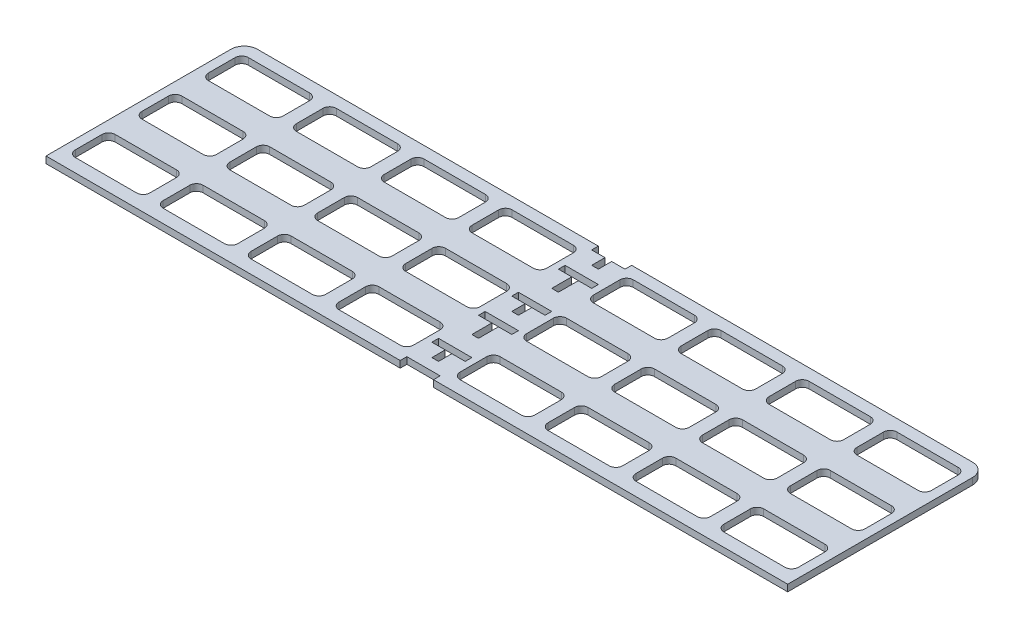
SolidWorks part; units mm, degrees
material "Balsa"
ref_plane "Front Plane" through (0, 0, 0) normal (0, 0, 1) x (1, 0, 0)
ref_plane "Top Plane" through (0, 0, 0) normal (0, 1, 0) x (1, 0, 0)
ref_plane "Right Plane" through (0, 0, 0) normal (1, 0, 0) x (0, 0, -1)
sketch "Sketch1" plane through (0, 0, 0) normal (0, 1, 0) x (1, 0, 0)
  line L0 (0, 0) -> (350.52, 0)
  line L1 (337.82, 188.976) -> (0, 188.976)
  line L3 (350.52, 0) -> (350.52, 176.276)
  line L4 (0, 188.976) -> (0, 169.926)
  line L5 (0, 169.926) -> (-3.175, 169.926)
  line L6 (-3.175, 169.926) -> (-3.175, 150.876)
  line L7 (-3.175, 150.876) -> (0, 150.876)
  line L8 (0, 150.876) -> (0, 131.826)
  line L9 (0, 131.826) -> (-3.175, 131.826)
  line L10 (-3.175, 131.826) -> (-3.175, 112.776)
  line L11 (-3.175, 112.776) -> (0, 112.776)
  line L12 (0, 112.776) -> (0, 93.726)
  line L13 (0, 93.726) -> (-3.175, 93.726)
  line L14 (-3.175, 93.726) -> (-3.175, 74.676)
  line L15 (-3.175, 74.676) -> (0, 74.676)
  line L16 (0, 74.676) -> (0, 55.626)
  line L17 (0, 55.626) -> (-3.175, 55.626)
  line L18 (-3.175, 55.626) -> (-3.175, 36.576)
  line L19 (-3.175, 36.576) -> (0, 36.576)
  line L20 (0, 36.576) -> (0, 17.526)
  line L21 (0, 17.526) -> (-3.175, 17.526)
  line L22 (-3.175, 17.526) -> (-3.175, 0)
  line L23 (-3.175, 0) -> (0, 0)
  arc A0 (337.82, 188.976) -> (350.52, 176.276) centre (337.82, 176.276) cw
  point P7 (350.52, 188.976)
  dimension "D4" = 12.7
  dimension "D2" = 350.52
  dimension "D3" = 188.976
  dimension "D5" = 19.05
  dimension "D6" = 19.05
  dimension "D7" = 3.175
  dimension "D8" = 19.05
  dimension "D9" = 19.05
  dimension "D10" = 19.05
  dimension "D11" = 19.05
  dimension "D12" = 19.05
  dimension "D13" = 19.05
  dimension "D14" = 3.175
  dimension "D15" = 3.175
  dimension "D16" = 3.175
  dimension "D17" = 3.175
  dimension "D18" = 337.82
  dimension "D19" = 3.175
  dimension "D20" = 19.05
  dimension "D21" = 3.175
  dimension "D22" = 176.276
  dimension "D23" = 3.175
extrude "Boss-Extrude1" add sketch "Sketch1" along normal blind 6.35
sketch "Sketch2" plane through (0, 6.35, 0) normal (0, 1, 0) x (1, 0, 0)
  line L68 (270.51, 19.05) -> (270.51, 44.45)
  line L69 (276.86, 12.7) -> (335.28, 12.7)
  line L70 (341.63, 19.05) -> (341.63, 44.45)
  line L71 (276.86, 50.8) -> (335.28, 50.8)
  line L72 (270.51, 82.55) -> (270.51, 107.95)
  line L73 (276.86, 76.2) -> (335.28, 76.2)
  line L74 (341.63, 82.55) -> (341.63, 107.95)
  line L76 (102.87, 19.05) -> (102.87, 44.45)
  line L77 (276.86, 114.3) -> (335.28, 114.3)
  line L78 (270.51, 146.05) -> (270.51, 171.45)
  line L79 (276.86, 139.7) -> (335.28, 139.7)
  line L80 (341.63, 146.05) -> (341.63, 171.45)
  line L81 (276.86, 177.8) -> (335.28, 177.8)
  line L91 (25.4, 12.7) -> (83.82, 12.7)
  line L92 (19.05, 19.05) -> (19.05, 44.45)
  line L93 (25.4, 50.8) -> (83.82, 50.8)
  line L94 (90.17, 19.05) -> (90.17, 44.45)
  line L95 (109.22, 12.7) -> (167.64, 12.7)
  line L96 (173.99, 19.05) -> (173.99, 44.45)
  line L97 (109.22, 50.8) -> (167.64, 50.8)
  line L98 (186.69, 19.05) -> (186.69, 44.45)
  line L99 (193.04, 12.7) -> (251.46, 12.7)
  line L100 (257.81, 19.05) -> (257.81, 44.45)
  line L101 (193.04, 50.8) -> (251.46, 50.8)
  line L102 (102.87, 82.55) -> (102.87, 107.95)
  line L103 (109.22, 76.2) -> (167.64, 76.2)
  line L104 (173.99, 82.55) -> (173.99, 107.95)
  line L105 (109.22, 114.3) -> (167.64, 114.3)
  line L106 (186.69, 82.55) -> (186.69, 107.95)
  line L107 (193.04, 76.2) -> (251.46, 76.2)
  line L108 (257.81, 82.55) -> (257.81, 107.95)
  line L109 (193.04, 114.3) -> (251.46, 114.3)
  line L110 (102.87, 146.05) -> (102.87, 171.45)
  line L111 (109.22, 139.7) -> (167.64, 139.7)
  line L112 (173.99, 146.05) -> (173.99, 171.45)
  line L113 (109.22, 177.8) -> (167.64, 177.8)
  line L114 (186.69, 146.05) -> (186.69, 171.45)
  line L115 (193.04, 139.7) -> (251.46, 139.7)
  line L116 (257.81, 146.05) -> (257.81, 171.45)
  line L117 (193.04, 177.8) -> (251.46, 177.8)
  line L118 (19.05, 82.55) -> (19.05, 107.95)
  line L119 (25.4, 76.2) -> (83.82, 76.2)
  line L120 (90.17, 82.55) -> (90.17, 107.95)
  line L121 (25.4, 114.3) -> (83.82, 114.3)
  line L122 (19.05, 146.05) -> (19.05, 171.45)
  line L123 (25.4, 139.7) -> (83.82, 139.7)
  line L124 (90.17, 146.05) -> (90.17, 171.45)
  line L125 (25.4, 177.8) -> (83.82, 177.8)
  line L126 (19.05, 19.05) -> (19.05, 82.55) construction
  arc A0 (83.82, 12.7) -> (90.17, 19.05) centre (83.82, 19.05) ccw
  arc A1 (25.4, 12.7) -> (19.05, 19.05) centre (25.4, 19.05) cw
  arc A2 (19.05, 44.45) -> (25.4, 50.8) centre (25.4, 44.45) cw
  arc A3 (83.82, 50.8) -> (90.17, 44.45) centre (83.82, 44.45) cw
  arc A4 (102.87, 44.45) -> (109.22, 50.8) centre (109.22, 44.45) cw
  arc A5 (109.22, 12.7) -> (102.87, 19.05) centre (109.22, 19.05) cw
  arc A6 (167.64, 12.7) -> (173.99, 19.05) centre (167.64, 19.05) ccw
  arc A7 (167.64, 50.8) -> (173.99, 44.45) centre (167.64, 44.45) cw
  arc A8 (186.69, 44.45) -> (193.04, 50.8) centre (193.04, 44.45) cw
  arc A9 (193.04, 12.7) -> (186.69, 19.05) centre (193.04, 19.05) cw
  arc A10 (251.46, 12.7) -> (257.81, 19.05) centre (251.46, 19.05) ccw
  arc A11 (251.46, 50.8) -> (257.81, 44.45) centre (251.46, 44.45) cw
  arc A12 (102.87, 107.95) -> (109.22, 114.3) centre (109.22, 107.95) cw
  arc A13 (109.22, 76.2) -> (102.87, 82.55) centre (109.22, 82.55) cw
  arc A14 (167.64, 76.2) -> (173.99, 82.55) centre (167.64, 82.55) ccw
  arc A15 (167.64, 114.3) -> (173.99, 107.95) centre (167.64, 107.95) cw
  arc A16 (186.69, 107.95) -> (193.04, 114.3) centre (193.04, 107.95) cw
  arc A17 (193.04, 76.2) -> (186.69, 82.55) centre (193.04, 82.55) cw
  arc A18 (251.46, 76.2) -> (257.81, 82.55) centre (251.46, 82.55) ccw
  arc A19 (251.46, 114.3) -> (257.81, 107.95) centre (251.46, 107.95) cw
  arc A20 (102.87, 171.45) -> (109.22, 177.8) centre (109.22, 171.45) cw
  arc A21 (109.22, 139.7) -> (102.87, 146.05) centre (109.22, 146.05) cw
  arc A22 (167.64, 139.7) -> (173.99, 146.05) centre (167.64, 146.05) ccw
  arc A23 (167.64, 177.8) -> (173.99, 171.45) centre (167.64, 171.45) cw
  arc A24 (186.69, 171.45) -> (193.04, 177.8) centre (193.04, 171.45) cw
  arc A25 (193.04, 139.7) -> (186.69, 146.05) centre (193.04, 146.05) cw
  arc A26 (251.46, 139.7) -> (257.81, 146.05) centre (251.46, 146.05) ccw
  arc A27 (251.46, 177.8) -> (257.81, 171.45) centre (251.46, 171.45) cw
  arc A28 (19.05, 107.95) -> (25.4, 114.3) centre (25.4, 107.95) cw
  arc A29 (25.4, 76.2) -> (19.05, 82.55) centre (25.4, 82.55) cw
  arc A30 (83.82, 76.2) -> (90.17, 82.55) centre (83.82, 82.55) ccw
  arc A31 (83.82, 114.3) -> (90.17, 107.95) centre (83.82, 107.95) cw
  arc A32 (19.05, 171.45) -> (25.4, 177.8) centre (25.4, 171.45) cw
  arc A33 (25.4, 139.7) -> (19.05, 146.05) centre (25.4, 146.05) cw
  arc A34 (83.82, 139.7) -> (90.17, 146.05) centre (83.82, 146.05) ccw
  arc A35 (83.82, 177.8) -> (90.17, 171.45) centre (83.82, 171.45) cw
  arc A36 (270.51, 44.45) -> (276.86, 50.8) centre (276.86, 44.45) cw
  arc A37 (276.86, 12.7) -> (270.51, 19.05) centre (276.86, 19.05) cw
  arc A38 (335.28, 12.7) -> (341.63, 19.05) centre (335.28, 19.05) ccw
  arc A39 (335.28, 50.8) -> (341.63, 44.45) centre (335.28, 44.45) cw
  arc A40 (270.51, 107.95) -> (276.86, 114.3) centre (276.86, 107.95) cw
  arc A41 (276.86, 76.2) -> (270.51, 82.55) centre (276.86, 82.55) cw
  arc A42 (335.28, 76.2) -> (341.63, 82.55) centre (335.28, 82.55) ccw
  arc A43 (335.28, 114.3) -> (341.63, 107.95) centre (335.28, 107.95) cw
  arc A44 (270.51, 171.45) -> (276.86, 177.8) centre (276.86, 171.45) cw
  arc A45 (276.86, 139.7) -> (270.51, 146.05) centre (276.86, 146.05) cw
  arc A46 (335.28, 139.7) -> (341.63, 146.05) centre (335.28, 146.05) ccw
  arc A47 (335.28, 177.8) -> (341.63, 171.45) centre (335.28, 171.45) cw
  point P10 (90.17, 12.7)
  point P13 (19.05, 12.7)
  point P16 (19.05, 50.8)
  point P19 (102.87, 31.75)
  dimension "D7" = 3
  dimension "D5" = 6.35
  dimension "D2" = 71.12
  dimension "D3" = 12.7
  dimension "D4" = 38.1
  dimension "D8" = 63.5
  dimension "D9" = 25.4
  dimension "D10" = 12.7
  dimension "D11" = 19.05
  dimension "D6" = 4
extrude "Weight Saving Holes" cut sketch "Sketch2" against normal up to surface (6.35 mm away) up to face at (43.9018, 0, -97.562)
mirror "Mirror1" about plane through (-3.175, 6.35, -93.726) normal (1, 0, 0) of "Weight Saving Holes", "Boss-Extrude1"
sketch "Sketch3" plane through (0, 6.35, 0) normal (0, 1, 0) x (1, 0, 0)
  line L8 (-19.05, 182.626) -> (12.7, 182.626)
  line L9 (-19.05, 182.626) -> (-19.05, 188.976)
  line L10 (-19.05, 188.976) -> (12.7, 188.976)
  line L11 (12.7, 182.626) -> (12.7, 188.976)
  line L12 (-19.05, 150.876) -> (12.7, 150.876)
  line L13 (-19.05, 150.876) -> (-19.05, 157.226)
  line L14 (-19.05, 157.226) -> (12.7, 157.226)
  line L15 (12.7, 150.876) -> (12.7, 157.226)
  line L16 (-19.05, 30.226) -> (12.7, 30.226)
  line L17 (-19.05, 30.226) -> (-19.05, 36.576)
  line L18 (-19.05, 36.576) -> (12.7, 36.576)
  line L19 (12.7, 30.226) -> (12.7, 36.576)
  line L20 (-19.05, 0) -> (12.7, 0)
  line L21 (-19.05, 0) -> (-19.05, 6.35)
  line L22 (-19.05, 6.35) -> (12.7, 6.35)
  line L23 (12.7, 0) -> (12.7, 6.35)
  line L24 (-19.05, 106.426) -> (12.7, 106.426)
  line L25 (-19.05, 106.426) -> (-19.05, 112.776)
  line L26 (-19.05, 112.776) -> (12.7, 112.776)
  line L27 (12.7, 106.426) -> (12.7, 112.776)
  line L28 (-19.05, 74.676) -> (12.7, 74.676)
  line L29 (-19.05, 74.676) -> (-19.05, 81.026)
  line L30 (-19.05, 81.026) -> (12.7, 81.026)
  line L31 (12.7, 74.676) -> (12.7, 81.026)
  line L32 (0, 169.926) -> (-6.35, 169.926) construction
  line L33 (337.82, 188.976) -> (0, 188.976) construction
  line L35 (-6.35, 150.876) -> (0, 150.876) construction
  line L36 (-6.35, 112.776) -> (0, 112.776) construction
  line L37 (-6.35, 74.676) -> (0, 74.676) construction
  line L38 (-6.35, 36.576) -> (0, 36.576) construction
  line L39 (-356.87, 0) -> (350.52, 0) construction
  point P0 (-3.175, 169.926)
  point P1 (-3.175, 188.976)
  point P4 (-3.175, 157.226)
  point P5 (-3.175, 112.776)
  point P6 (-3.175, 81.026)
  point P7 (-3.175, 36.576)
  point P24 (-3.175, 6.35)
  dimension "D5" = 31.75
  dimension "D6" = 6.35
  dimension "D7" = 31.75
  dimension "D8" = 6.35
  dimension "D9" = 31.75
  dimension "D10" = 6.35
  dimension "D11" = 31.75
  dimension "D12" = 6.35
  dimension "D13" = 31.75
  dimension "D14" = 6.35
  dimension "D15" = 31.75
  dimension "D16" = 6.35
extrude "Boom Bracket Attachment Slots" cut sketch "Sketch3" against normal through all
equation "\"D7@Sketch3\"=\"D5@Sketch3\""
equation "\"D13@Sketch3\"=\"D5@Sketch3\""
equation "\"D15@Sketch3\"=\"D5@Sketch3\""
equation "\"D9@Sketch3\"=\"D5@Sketch3\""
equation "\"D11@Sketch3\"=\"D5@Sketch3\""
